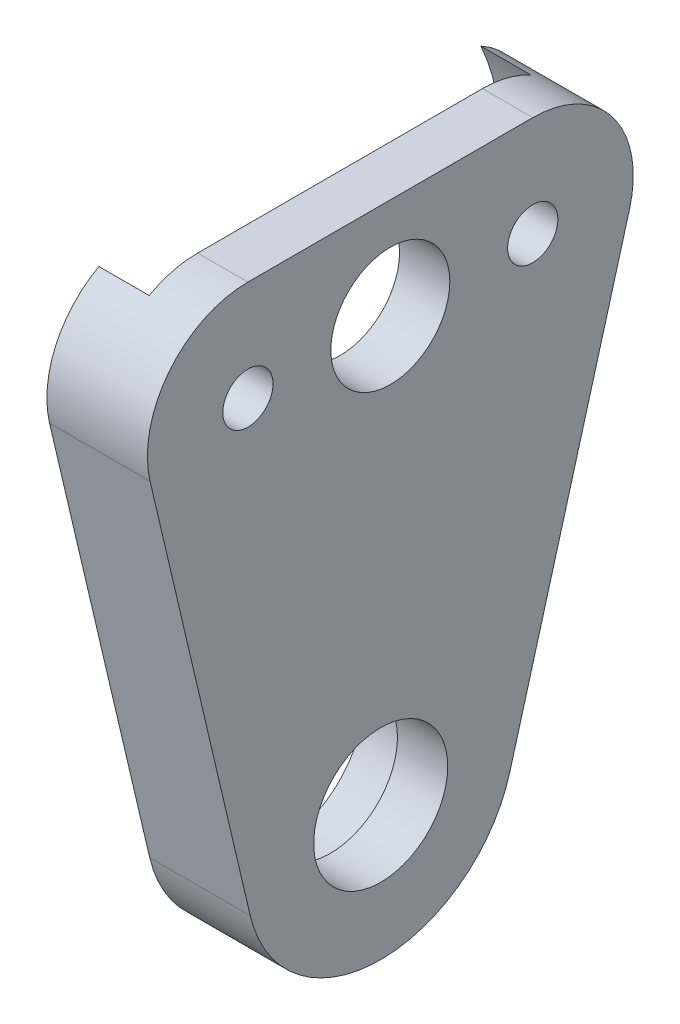
SolidWorks part; units mm, degrees
ref_plane "Front Plane" through (0, 0, 0) normal (0, 0, 1) x (1, 0, 0)
ref_plane "Top Plane" through (0, 0, 0) normal (0, 1, 0) x (1, 0, 0)
ref_plane "Right Plane" through (0, 0, 0) normal (1, 0, 0) x (0, 0, -1)
sketch "Sketch1" plane through (0, 0, 0) normal (1, 0, 0) x (0, 0, -1)
  line L0 (30.4317, 18) -> (13.4317, 18)
  line L1 (7.5908, 10.6277) -> (13.5702, -14.8231)
  line L2 (29.062, -15.15) -> (36.2096, 10.3825)
  line L3 (30.4317, 12) -> (13.4317, 12) construction
  line L6 (-9, -42) -> (51, -42) construction
  line L7 (-9, -42) -> (-9, 16) construction
  line L8 (-9, 16) -> (51, 16) construction
  line L9 (51, -42) -> (51, 16) construction
  arc A0 (36.2096, 10.3825) -> (30.4317, 18) centre (30.4317, 12) ccw
  circle A1 centre (21.9317, 12) radius 12.5 construction
  arc A2 (13.4317, 18) -> (7.5908, 10.6277) centre (13.4317, 12) ccw
  circle A3 centre (21.9317, 12) radius 3.55
  circle A4 centre (41, 0) radius 6 construction
  circle A5 centre (0, 0) radius 4 construction
  arc A6 (13.5702, -14.8231) -> (29.062, -15.15) centre (21.3582, -12.9934) ccw
  circle A7 centre (30.4317, 12) radius 1.5
  circle A8 centre (13.4317, 12) radius 1.5
  circle A9 centre (30.4317, 12) radius 3.25 construction
  circle A10 centre (13.4317, 12) radius 3.25 construction
  circle A12 centre (21.3582, -12.9934) radius 4
  dimension "D5" = 6
  dimension "D6" = 8
  dimension "D7" = 8
  dimension "D8" = 25
  dimension "D10" = 7.1
  dimension "D15" = 3
  dimension "D17" = 6.5
  dimension "D20" = 12
  dimension "D25" = 8
  dimension "D1" = 60
  dimension "D2" = 58
  dimension "D3" = 42
  dimension "D4" = 9
  dimension "D9" = 12
  dimension "D11" = 25
  dimension "D12" = 42
  dimension "D13" = 50
  dimension "D16" = 8.5
  dimension "D22" = 25
  dimension "D24" = 25
extrude "Boss-Extrude1" add sketch "Sketch1" along normal blind 6
sketch "Sketch2" plane through (0, 0, 0) normal (1, 0, 0) x (0, 0, -1)
  circle A0 centre (21.3582, -12.9934) radius 4.99
  dimension "D1" = 9.98
extrude "Cut-Extrude1" cut sketch "Sketch2" along normal blind 3
sketch "Sketch3" plane through (0, 0, 0) normal (1, 0, 0) x (0, 0, -1)
  circle A0 centre (21.9317, 12) radius 12.55
  dimension "D1" = 25.1
extrude "Cut-Extrude2" cut sketch "Sketch3" along normal blind 3
